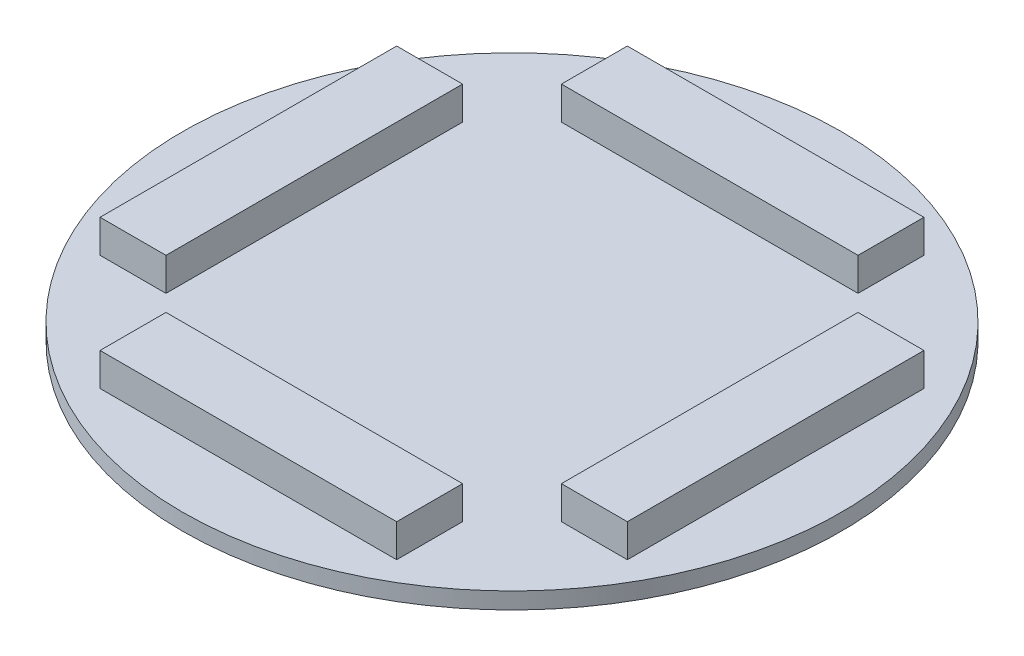
SolidWorks part; units mm, degrees
material "A-Glass Fiber"
ref_plane "Front Plane" through (0, 0, 0) normal (0, 0, 1) x (1, 0, 0)
ref_plane "Top Plane" through (0, 0, 0) normal (0, 1, 0) x (1, 0, 0)
ref_plane "Right Plane" through (0, 0, 0) normal (1, 0, 0) x (0, 0, -1)
sketch "Sketch1" plane through (0, 0, 0) normal (0, 1, 0) x (1, 0, 0)
  circle A0 centre (0, 0) radius 20
  dimension "D1" = 40
extrude "PCB" add sketch "Sketch1" along normal blind 1
sketch "Sketch2" plane through (0, 1, 0) normal (0, 1, 0) x (1, 0, 0)
  line L0 (0, 20) -> (0, 0) construction
  line L1 (-9, 16) -> (9, 16)
  line L2 (-9, 16) -> (-9, 12)
  line L3 (-9, 12) -> (9, 12)
  line L4 (9, 16) -> (9, 12)
  circle A0 centre (0, 0) radius 20 construction
  point P9 (0, 16)
  dimension "D1" = 4
  dimension "D2" = 18
  dimension "D3" = 16
extrude "Hirose Connector Stack" add sketch "Sketch2" along normal blind 2 contours L1 L4 L3 L2
pattern_circular "CirPattern1" count 4 over 360 about axis through (0, 0, 0) along (0, 1, 0) of "Hirose Connector Stack"
